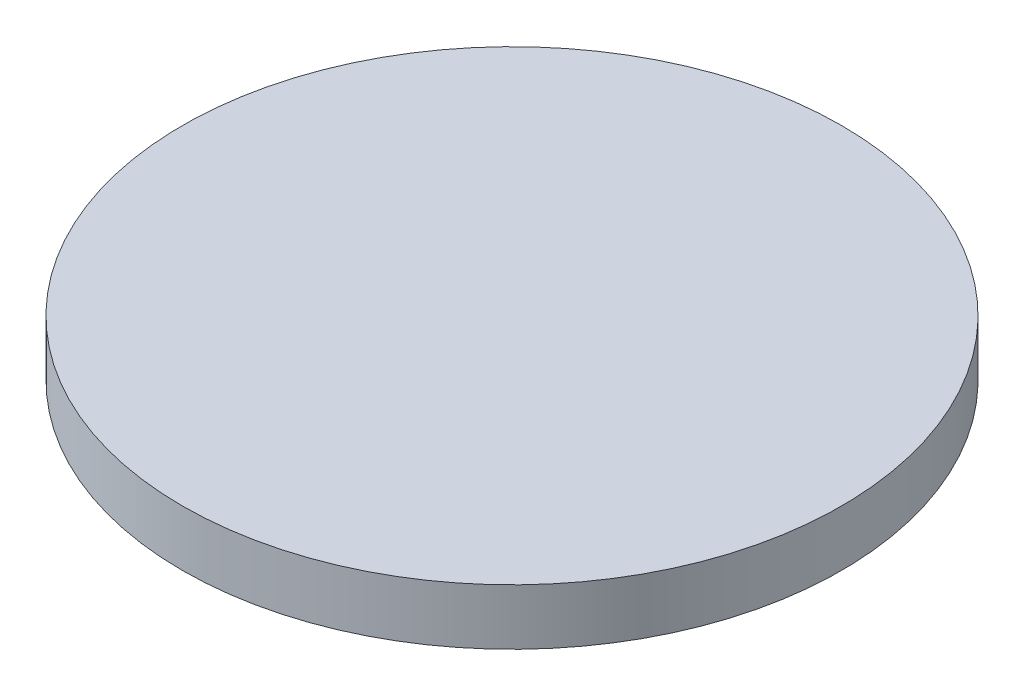
SolidWorks part; units mm, degrees
ref_plane "Front Plane" through (0, 0, 0) normal (0, 0, 1) x (1, 0, 0)
ref_plane "Top Plane" through (0, 0, 0) normal (0, 1, 0) x (1, 0, 0)
ref_plane "Right Plane" through (0, 0, 0) normal (1, 0, 0) x (0, 0, -1)
sketch "Sketch1" plane through (0, 0, 0) normal (0, 1, 0) x (1, 0, 0)
  circle A0 centre (0, 0) radius 37.465
  dimension "D1" = 74.93
extrude "Boss-Extrude1" add sketch "Sketch1" along normal blind 6.35
